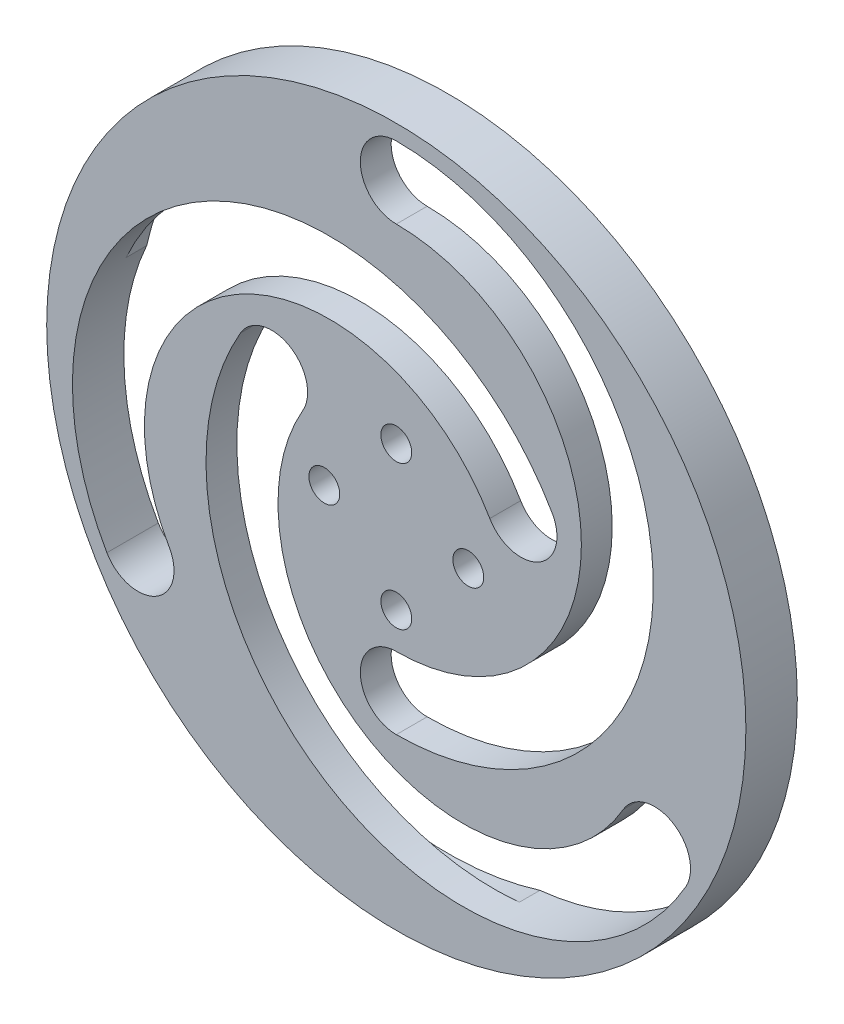
SolidWorks part; units mm, degrees
ref_plane "Front Plane" through (0, 0, 0) normal (0, 0, 1) x (1, 0, 0)
ref_plane "Top Plane" through (0, 0, 0) normal (0, 1, 0) x (1, 0, 0)
ref_plane "Right Plane" through (0, 0, 0) normal (1, 0, 0) x (0, 0, -1)
sketch "Sketch2" plane through (0, 0, 0) normal (0, 0, 1) x (1, 0, 0)
  circle A0 centre (0, 0) radius 34
  dimension "D1" = 68
extrude "Boss-Extrude1" add sketch "Sketch2" along normal blind 5
sketch "Sketch3" plane through (0, 0, 5) normal (0, 0, 1) x (1, 0, 0)
  line L0 (0, 0) -> (0, 29) construction
  line L1 (0, 0) -> (0, -14) construction
  line L2 (0, -14) -> (0, 7.5) construction
  arc A0 (0, 29) -> (0, -14) centre (0, 7.5) cw
  arc A1 (25.1147, -14.5) -> (-12.1244, 7) centre (6.4952, -3.75) cw
  arc A2 (-25.1147, -14.5) -> (12.1244, 7) centre (-6.4952, -3.75) cw
  point P15 (0, 0)
  dimension "D1" = 29
  dimension "D2" = 14
  dimension "D3" = 21.5
  dimension "D4" = 3
extrude "Cut-Extrude-Thin1" cut sketch "Sketch3" against normal up to next thin thin type mid plane wall 7
fillet "Fillet1" [suppressed] radius 3.5
sketch "Sketch7" plane through (0, 0, 0) normal (0, 0, -1) x (-1, 0, 0)
  line L0 (0, 0) -> (7, 0) construction
  circle A0 centre (7, 0) radius 1.5
  circle A2 centre (0, -7) radius 1.5
  circle A3 centre (-7, 0) radius 1.5
  circle A4 centre (0, 7) radius 1.5
  point P13 (0, 0)
  dimension "D2" = 3
  dimension "D1" = 7
  dimension "D3" = 4
extrude "Cut-Extrude1" cut sketch "Sketch7" against normal up to next
sketch "Sketch8" plane through (0, 0, 0) normal (0, 0, -1) x (-1, 0, 0)
  line L0 (0, 32.5) -> (0, 25.5) construction
  line L1 (-9.0933, 5.25) -> (-15.1554, 8.75) construction
  line L2 (9.0933, 5.25) -> (15.1554, 8.75) construction
  line L3 (28.1458, -16.25) -> (22.0836, -12.75) construction
  line L4 (-28.1458, -16.25) -> (-22.0836, -12.75) construction
  line L5 (0, -10.5) -> (0, -17.5) construction
  circle A0 centre (0, 29) radius 3.5
  circle A1 centre (-12.1244, 7) radius 3.5
  circle A2 centre (12.1244, 7) radius 3.5
  circle A3 centre (25.1147, -14.5) radius 3.5
  circle A4 centre (-25.1147, -14.5) radius 3.5
  circle A5 centre (0, -14) radius 3.5
extrude "Cut-Extrude2" cut sketch "Sketch8" against normal up to next
sketch "Sketch9" plane through (0, 0, 0) normal (0, 0, -1) x (-1, 0, 0)
  circle A0 centre (0, 0) radius 30
  circle A1 centre (0, 0) radius 34 construction
  dimension "D1" = 4
extrude "Cut-Extrude3" cut sketch "Sketch9" against normal blind 2
